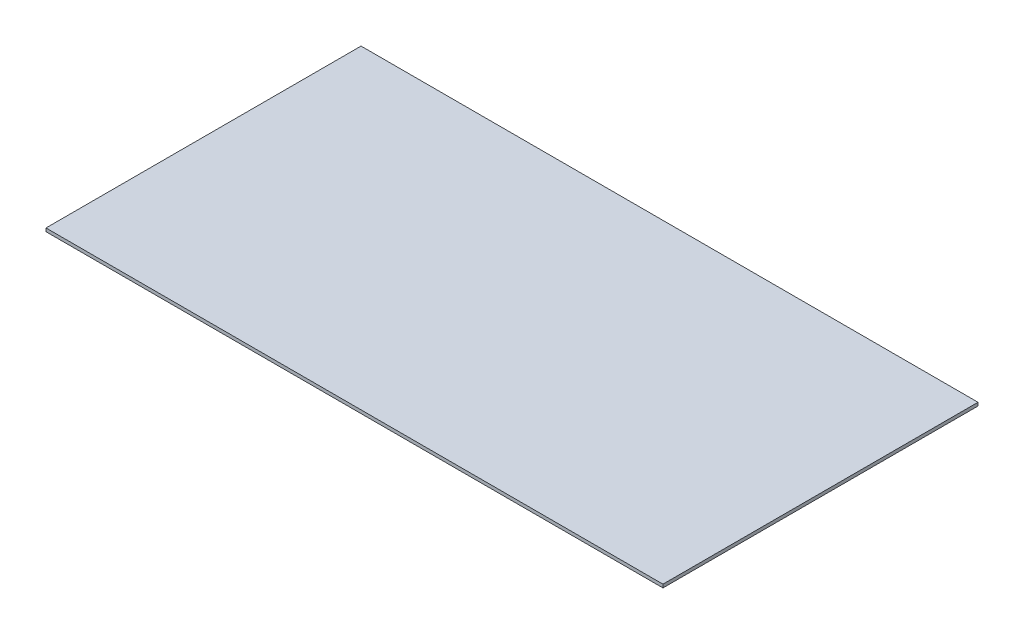
SolidWorks part; units mm, degrees
ref_plane "Front Plane" through (0, 0, 0) normal (0, 0, 1) x (1, 0, 0)
ref_plane "Top Plane" through (0, 0, 0) normal (0, 1, 0) x (1, 0, 0)
ref_plane "Right Plane" through (0, 0, 0) normal (1, 0, 0) x (0, 0, -1)
sketch "Sketch1" plane through (0, 0, 0) normal (0, 1, 0) x (1, 0, 0)
  line L1 (-596.9, -304.8) -> (596.9, -304.8)
  line L2 (-596.9, -304.8) -> (-596.9, 304.8)
  line L3 (-596.9, 304.8) -> (596.9, 304.8)
  line L4 (596.9, -304.8) -> (596.9, 304.8)
  line L5 (-596.9, -304.8) -> (596.9, 304.8) construction
  line L6 (-596.9, 304.8) -> (596.9, -304.8) construction
  point P0 (0, 0)
  dimension "D1" = 1193.8
  dimension "D2" = 609.6
extrude "Boss-Extrude1" add sketch "Sketch1" along normal blind 6.35
